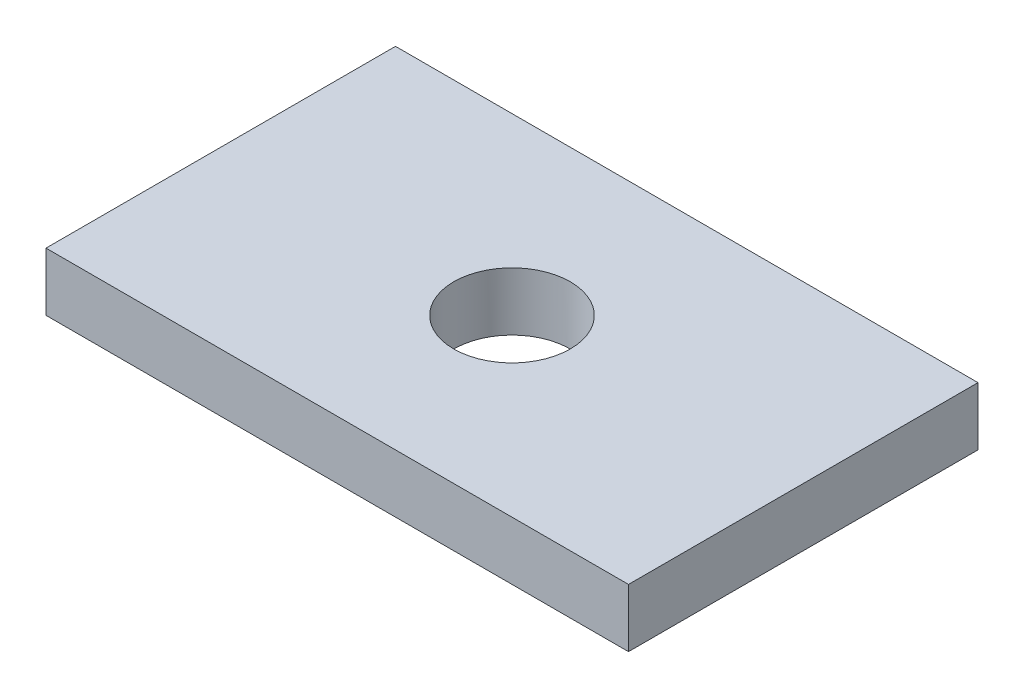
SolidWorks part; units mm, degrees
ref_plane "Front Plane" through (0, 0, 0) normal (0, 0, 1) x (1, 0, 0)
ref_plane "Top Plane" through (0, 0, 0) normal (0, 1, 0) x (1, 0, 0)
ref_plane "Right Plane" through (0, 0, 0) normal (1, 0, 0) x (0, 0, -1)
sketch "Sketch1" plane through (0, 0, 0) normal (0, 1, 0) x (1, 0, 0)
  line L1 (-63.5, -38.1) -> (63.5, -38.1)
  line L2 (-63.5, -38.1) -> (-63.5, 38.1)
  line L3 (-63.5, 38.1) -> (63.5, 38.1)
  line L4 (63.5, -38.1) -> (63.5, 38.1)
  line L5 (-63.5, -38.1) -> (63.5, 38.1) construction
  line L6 (-63.5, 38.1) -> (63.5, -38.1) construction
  point P0 (0, 0)
  dimension "D1" = 76.2
  dimension "D2" = 127
extrude "Boss-Extrude1" add sketch "Sketch1" along normal blind 12.7
sketch "Sketch2" plane through (0, 12.7, 0) normal (0, 1, 0) x (1, 0, 0)
  circle A0 centre (0, 0) radius 12.7
  dimension "D1" = 25.4
extrude "Cut-Extrude1" cut sketch "Sketch2" against normal through all both and the other way through all
